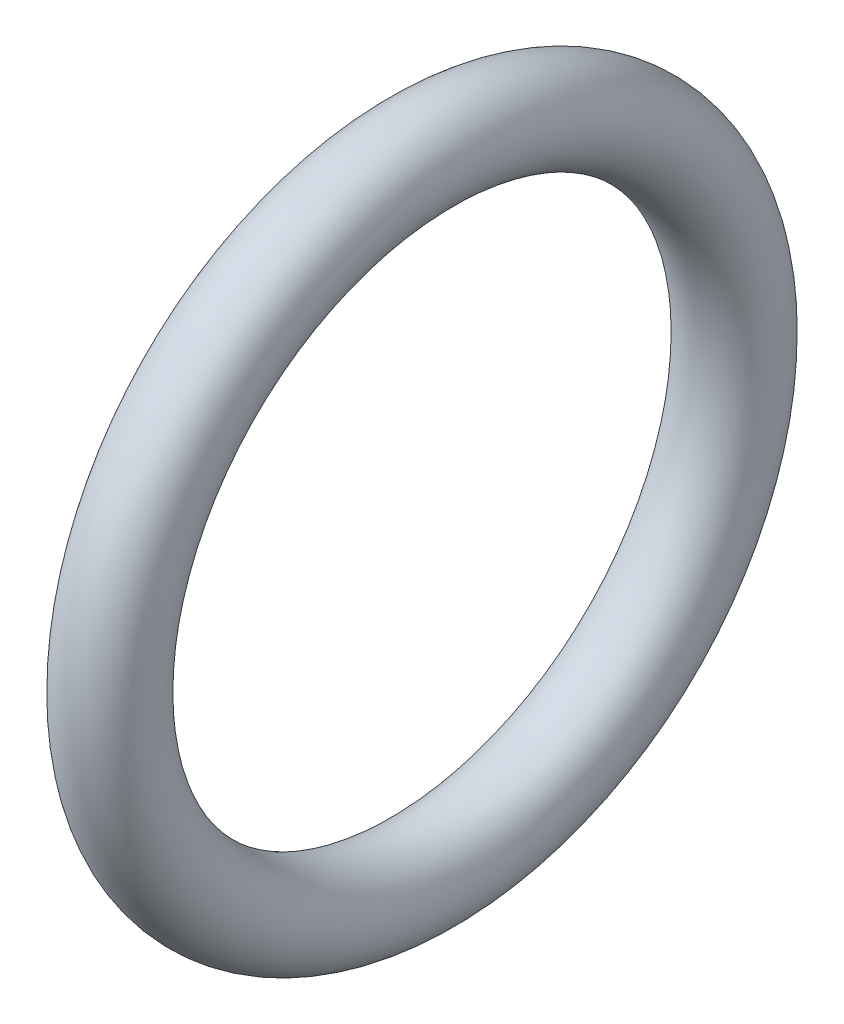
SolidWorks part; units mm, degrees
ref_plane "Face" through (0, 0, 0) normal (0, 0, 1) x (1, 0, 0)
ref_plane "Dessus" through (0, 0, 0) normal (0, 1, 0) x (1, 0, 0)
ref_plane "Droite" through (0, 0, 0) normal (1, 0, 0) x (0, 0, -1)
sketch "Esquisse1" plane through (0, 0, 0) normal (0, 0, 1) x (1, 0, 0)
  line L0 (-17.272, 0) -> (18.3083, 0) construction
  circle A0 centre (0, 10.5) radius 1.5
  dimension "D1" = 3
  dimension "D2" = 10.5
revolve "Révolution1" add sketch "Esquisse1" angle 360 about L0
